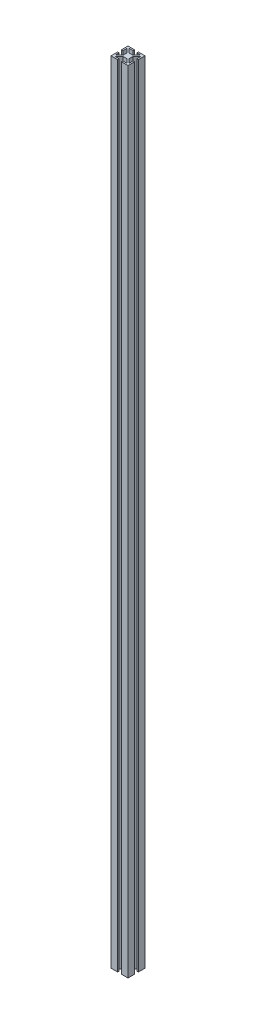
SolidWorks part; units mm, degrees
ref_plane "Front Plane" through (0, 0, 0) normal (0, 0, 1) x (1, 0, 0)
ref_plane "Top Plane" through (0, 0, 0) normal (0, 1, 0) x (1, 0, 0)
ref_plane "Right Plane" through (0, 0, 0) normal (1, 0, 0) x (0, 0, -1)
sketch "Sketch1" plane through (11.365, 0, 9.8462) normal (0, 1, 0) x (1, 0, 0)
  line L0 (-11.365, 9.8462) -> (-11.365, 32.3924) construction
  line L1 (-11.365, 9.8462) -> (-35.43, 9.8462) construction
  line L2 (-11.365, 9.8462) -> (-7.5972, 6.0784) construction
  line L3 (-24.065, 22.5462) -> (-14.2298, 22.5462)
  line L4 (-14.2298, 22.5462) -> (-14.2298, 20.3364)
  line L5 (-14.2298, 20.3364) -> (-20.2926, 20.3364)
  line L6 (-20.2926, 20.3364) -> (-14.3109, 14.3547)
  line L7 (-14.3109, 14.3547) -> (-8.4191, 14.3547)
  line L8 (-15.8735, 12.7921) -> (-15.8735, 6.9003)
  line L9 (-21.8552, 18.7738) -> (-15.8735, 12.7921)
  line L10 (-21.8552, 12.711) -> (-21.8552, 18.7738)
  line L11 (-24.065, 12.711) -> (-21.8552, 12.711)
  line L12 (-24.065, 22.5462) -> (-24.065, 12.711)
  line L13 (-14.3109, 5.3377) -> (-8.4191, 5.3377)
  line L14 (-20.2926, -0.644) -> (-14.3109, 5.3377)
  line L15 (-21.8552, 0.9186) -> (-15.8735, 6.9003)
  line L16 (-21.8552, 6.9814) -> (-21.8552, 0.9186)
  line L17 (-24.065, 6.9814) -> (-21.8552, 6.9814)
  line L18 (-24.065, -2.8538) -> (-24.065, 6.9814)
  line L19 (-14.2298, -0.644) -> (-20.2926, -0.644)
  line L20 (-14.2298, -2.8538) -> (-14.2298, -0.644)
  line L21 (-24.065, -2.8538) -> (-14.2298, -2.8538)
  line L22 (1.335, -2.8538) -> (-8.5002, -2.8538)
  line L23 (-8.5002, -2.8538) -> (-8.5002, -0.644)
  line L24 (-8.5002, -0.644) -> (-2.4374, -0.644)
  line L25 (1.335, -2.8538) -> (1.335, 6.9814)
  line L26 (1.335, 6.9814) -> (-0.8748, 6.9814)
  line L27 (-0.8748, 6.9814) -> (-0.8748, 0.9186)
  line L28 (-0.8748, 0.9186) -> (-6.8565, 6.9003)
  line L29 (-2.4374, -0.644) -> (-8.4191, 5.3377)
  line L30 (1.335, 22.5462) -> (1.335, 12.711)
  line L31 (1.335, 12.711) -> (-0.8748, 12.711)
  line L32 (-0.8748, 12.711) -> (-0.8748, 18.7738)
  line L33 (-0.8748, 18.7738) -> (-6.8565, 12.7921)
  line L34 (-6.8565, 12.7921) -> (-6.8565, 6.9003)
  line L35 (-2.4374, 20.3364) -> (-8.4191, 14.3547)
  line L36 (-8.5002, 20.3364) -> (-2.4374, 20.3364)
  line L37 (-8.5002, 22.5462) -> (-8.5002, 20.3364)
  line L38 (1.335, 22.5462) -> (-8.5002, 22.5462)
  point P20 (-15.8735, 9.8462)
  point P26 (-6.8565, 9.8462)
  point P36 (-11.365, 5.3377)
  point P42 (-11.365, 14.3547)
  dimension "D1" = 9.8352
  dimension "D2" = 12.7
  dimension "D3" = 4.5085
  dimension "D4" = 2.2098
  dimension "D5" = 1.1049
extrude "Boss-Extrude1" add sketch "Sketch1" along normal blind 1181.1
other "1010<1>"
